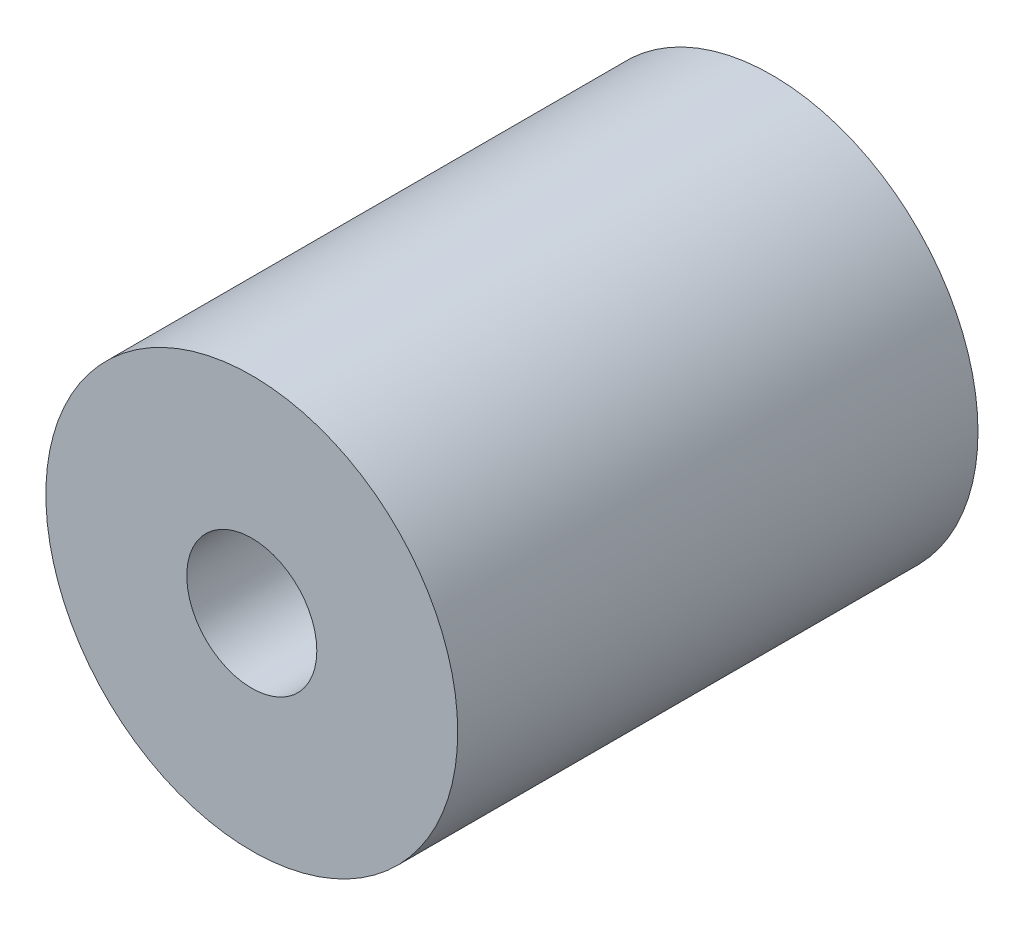
SolidWorks part; units mm, degrees
ref_plane "Alzado" through (0, 0, 0) normal (0, 0, 1) x (1, 0, 0)
ref_plane "Planta" through (0, 0, 0) normal (0, 1, 0) x (1, 0, 0)
ref_plane "Vista lateral" through (0, 0, 0) normal (1, 0, 0) x (0, 0, -1)
sketch "Croquis1" plane through (0, 0, 0) normal (0, 0, 1) x (1, 0, 0)
  circle A0 centre (0, 0) radius 9.5
  circle A1 centre (0, 0) radius 3
  dimension "D1" = 19
  dimension "D2" = 6
extrude "Saliente-Extruir1" add sketch "Croquis1" along normal blind 24
